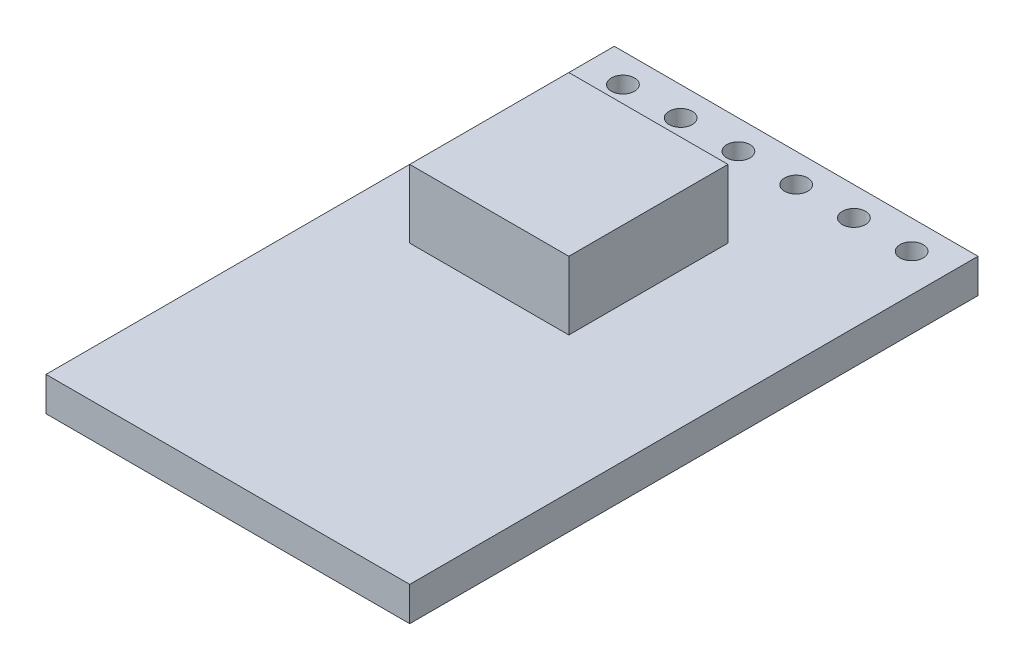
SolidWorks part; units mm, degrees
ref_plane "Piano frontale" through (0, 0, 0) normal (0, 0, 1) x (1, 0, 0)
ref_plane "Piano superiore" through (0, 0, 0) normal (0, 1, 0) x (1, 0, 0)
ref_plane "Piano destro" through (0, 0, 0) normal (1, 0, 0) x (0, 0, -1)
sketch "Schizzo1" plane through (0, 0, 0) normal (0, 1, 0) x (1, 0, 0)
  line L1 (0, 0) -> (-16, 0)
  line L2 (0, 0) -> (0, 25)
  line L3 (0, 25) -> (-16, 25)
  line L4 (-16, 0) -> (-16, 25)
  dimension "D1" = 16
  dimension "D2" = 25
extrude "Estrusione-Estrusione1" add sketch "Schizzo1" along normal blind 1.5
sketch "Schizzo2" plane through (0, 1.5, 0) normal (0, 1, 0) x (1, 0, 0)
  line L0 (-14.35, 23.73) -> (-1.65, 23.73) construction
  line L1 (0, 25) -> (-16, 25) construction
  line L2 (-8, 23.73) -> (-8, 25) construction
  circle A0 centre (-14.35, 23.73) radius 0.51
  circle A1 centre (-11.81, 23.73) radius 0.51
  circle A2 centre (-9.27, 23.73) radius 0.51
  circle A3 centre (-6.73, 23.73) radius 0.51
  circle A4 centre (-4.19, 23.73) radius 0.51
  circle A5 centre (-1.65, 23.73) radius 0.51
  dimension "D1" = 1.02
  dimension "D2" = 2.54
  dimension "D3" = 2.54
  dimension "D4" = 2.54
  dimension "D5" = 2.54
  dimension "D6" = 2.54
  dimension "D7" = 1.27
extrude "Taglio-Estrusione1" cut sketch "Schizzo2" against normal blind 1.5
sketch "Schizzo3" plane through (0, 1.5, 0) normal (0, 1, 0) x (1, 0, 0)
  line L0 (0, 25) -> (-16, 25) construction
  line L1 (-13, 20) -> (-6, 20)
  line L2 (-13, 20) -> (-13, 13)
  line L3 (-13, 13) -> (-6, 13)
  line L4 (-6, 20) -> (-6, 13)
  line L5 (-16, 25) -> (-16, 0) construction
  dimension "D1" = 5
  dimension "D2" = 3
  dimension "D3" = 7
extrude "Estrusione-Estrusione2" add sketch "Schizzo3" along normal blind 3
